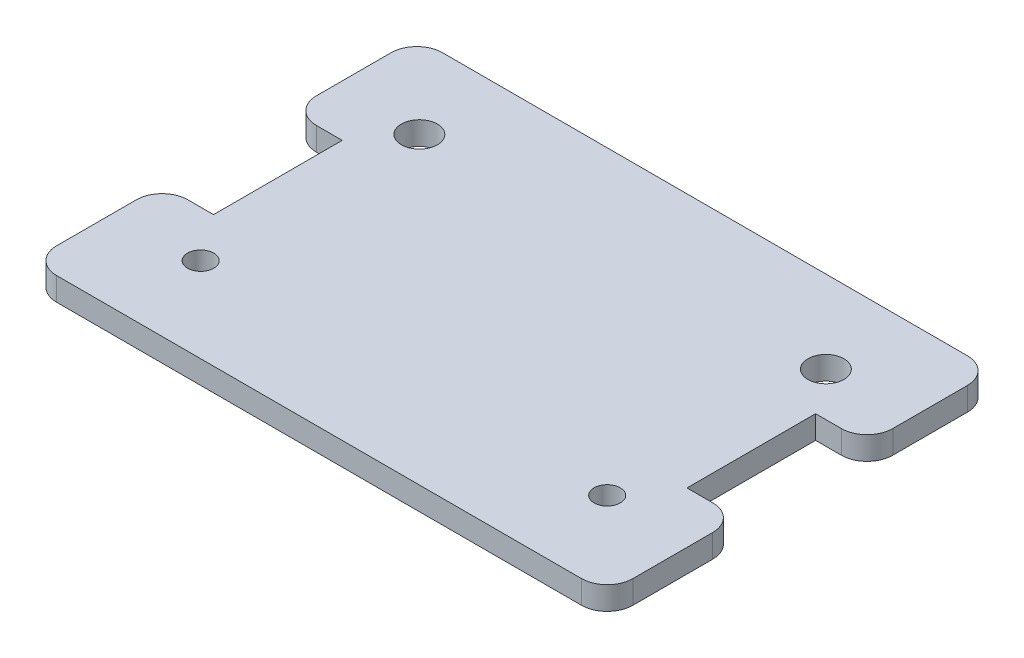
SolidWorks part; units mm, degrees
ref_plane "Front Plane" through (0, 0, 0) normal (0, 0, 1) x (1, 0, 0)
ref_plane "Top Plane" through (0, 0, 0) normal (0, 1, 0) x (1, 0, 0)
ref_plane "Right Plane" through (0, 0, 0) normal (1, 0, 0) x (0, 0, -1)
sketch "Sketch1" plane through (0, 0, 0) normal (0, 1, 0) x (1, 0, 0)
  line L1 (0, 0) -> (112, 0)
  line L2 (0, 0) -> (0, 75)
  line L3 (0, 75) -> (112, 75)
  line L4 (112, 0) -> (112, 75)
  dimension "D1" = 112
  dimension "D2" = 75
extrude "Boss-Extrude1" add sketch "Sketch1" along normal blind 4.5
sketch "Sketch2" plane through (0, 4.5, 0) normal (0, 1, 0) x (1, 0, 0)
  line L0 (16.5, 16.5) -> (95.5, 16.5) construction
  line L1 (0, 0) -> (112, 0) construction
  line L2 (112, 0) -> (112, 75) construction
  line L3 (0, 75) -> (0, 0) construction
  line L4 (16.5, 59) -> (16.5, 16.5) construction
  line L5 (16.5, 59) -> (95.5, 59) construction
  line L6 (95.5, 59) -> (95.5, 16.5) construction
  line L9 (0, 25.5) -> (10, 25.5)
  line L10 (0, 25.5) -> (0, 50.5)
  line L11 (0, 50.5) -> (10, 50.5)
  line L12 (10, 25.5) -> (10, 50.5)
  line L13 (112, 25.5) -> (102, 25.5)
  line L14 (112, 25.5) -> (112, 50.5)
  line L15 (112, 50.5) -> (102, 50.5)
  line L16 (102, 25.5) -> (102, 50.5)
  circle A0 centre (95.5, 16.5) radius 2.55
  circle A1 centre (16.5, 16.5) radius 2.55
  circle A2 centre (16.5, 59) radius 3.5
  circle A3 centre (95.5, 59) radius 3.5
  dimension "D2" = 16.5
  dimension "D3" = 16.5
  dimension "D5" = 7
  dimension "D6" = 7
  dimension "D7" = 5.1
  dimension "D8" = 5.1
  dimension "D1" = 16.5
  dimension "D4" = 59
  dimension "D9" = 25.5
  dimension "D10" = 25.5
  dimension "D11" = 25
  dimension "D12" = 25
  dimension "D13" = 10
  dimension "D14" = 10
extrude "Cut-Extrude1" cut sketch "Sketch2" against normal through all
fillet "Fillet1" radius 5 8 edges at (112, 2.25, 0) (112, 2.25, -25.5) (112, 2.25, -50.5) (112, 2.25, -75) (0, 2.25, 0) (0, 2.25, -25.5) (0, 2.25, -50.5) (0, 2.25, -75)
